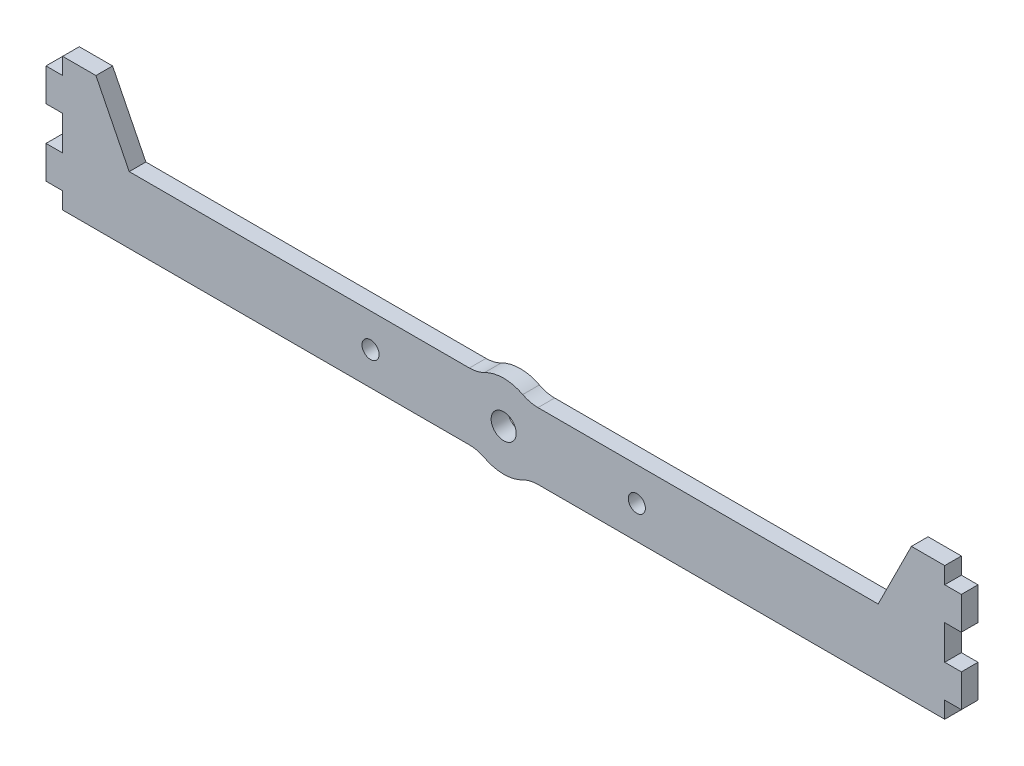
SolidWorks part; units mm, degrees
ref_plane "Front Plane" through (0, 0, 0) normal (0, 0, 1) x (1, 0, 0)
ref_plane "Top Plane" through (0, 0, 0) normal (0, 1, 0) x (1, 0, 0)
ref_plane "Right Plane" through (0, 0, 0) normal (1, 0, 0) x (0, 0, -1)
sketch "Sketch1" plane through (0, 0, 0) normal (0, 0, 1) x (1, 0, 0)
  line L0 (-168.275, -12.7) -> (-168.275, -6.35)
  line L1 (142.875, -12.7) -> (9.525, -12.7)
  line L2 (-142.875, -12.7) -> (-168.275, -12.7)
  line L3 (142.875, 12.7) -> (9.525, 12.7)
  line L4 (-168.275, 12.7) -> (-168.275, 19.25)
  line L5 (168.275, -12.7) -> (-168.275, 12.7) construction
  line L6 (168.275, 12.7) -> (-168.275, -12.7) construction
  line L7 (-168.275, 38.1) -> (-155.575, 38.1)
  line L8 (-155.575, 38.1) -> (-142.875, 12.7)
  line L9 (168.275, 0) -> (-168.275, 0) construction
  line L10 (-168.275, -6.35) -> (-174.625, -6.35)
  line L11 (-168.275, 31.75) -> (-174.625, 31.75)
  line L12 (168.275, -12.7) -> (168.275, -6.35)
  line L13 (0, 12.7) -> (0, -12.7) construction
  line L14 (-168.275, 19.25) -> (-174.625, 19.25)
  line L15 (-174.625, 31.75) -> (-174.625, 19.25)
  line L16 (-174.625, -6.35) -> (-174.625, 6.15)
  line L17 (-168.275, 6.15) -> (-174.625, 6.15)
  line L18 (-168.275, 6.15) -> (-168.275, 12.7)
  line L19 (-168.275, 31.75) -> (-168.275, 38.1)
  line L20 (168.275, -6.35) -> (174.625, -6.35)
  line L21 (174.625, -6.35) -> (174.625, 6.15)
  line L22 (168.275, 6.15) -> (174.625, 6.15)
  line L23 (168.275, 6.15) -> (168.275, 12.7)
  line L24 (168.275, 12.7) -> (168.275, 19.25)
  line L25 (174.625, 31.75) -> (174.625, 19.25)
  line L26 (168.275, 19.25) -> (174.625, 19.25)
  line L27 (168.275, 31.75) -> (174.625, 31.75)
  line L28 (168.275, 31.75) -> (168.275, 38.1)
  line L29 (168.275, 38.1) -> (155.575, 38.1)
  line L30 (155.575, 38.1) -> (142.875, 12.7)
  line L31 (142.875, -12.7) -> (168.275, -12.7)
  line L32 (-9.525, 12.7) -> (-142.875, 12.7)
  line L33 (-9.525, -12.7) -> (-142.875, -12.7)
  arc A0 (9.525, 12.7) -> (-9.525, 12.7) centre (0, 0) ccw
  arc A1 (-9.525, -12.7) -> (9.525, -12.7) centre (0, 0) ccw
  point P0 (0, 0)
  dimension "D1" = 25.4
  dimension "D2" = 336.55
  dimension "D3" = 25.4
  dimension "D4" = 6.35
  dimension "D5" = 12.5
  dimension "D6" = 6.35
  dimension "D7" = 25.4
extrude "Boss-Extrude1" add sketch "Sketch1" along normal blind 6.35
hole_wizard "V (0.377) Diameter Hole1" positions "Sketch3" profile "Sketch2" hole size "V" standard "ANSI Inch" end condition through all
sketch "Sketch3" plane through (0, 0, 6.35) normal (0, 0, 1) x (1, 0, 0)
  point P0 (0, 0)
sketch "Sketch2" plane through (0, 0, 6.35) normal (1, 0, 0) x (0, -1, 0)
  line L0 (0, 0) -> (0, 6.35)
  line L1 (0, 6.35) -> (4.7879, 6.35)
  line L2 (4.7879, 6.35) -> (4.7879, 0)
  line L5 (4.7879, 0) -> (0, 0)
  line L11 (0, -6.35) -> (0, 107.95) construction
  dimension "Thru Hole Dia." = 9.5758
  dimension "Thru Hole Depth" = 6.35
fillet "Fillet1" [suppressed] radius 2.54
fillet "Fillet2" radius 12.7 4 edges at (-9.525, -12.7, 3.175) (9.525, -12.7, 3.175) (9.525, 12.7, 3.175) (-9.525, 12.7, 3.175)
hole_wizard "F (0.257) Diameter Hole1" positions "Sketch5" profile "Sketch4" hole size "F" standard "ANSI Inch" end condition through all
sketch "Sketch5" plane through (0, 0, 6.35) normal (0, 0, 1) x (1, 0, 0)
  line L0 (-174.625, -0.1) -> (174.625, -0.1) construction
  line L1 (-174.625, -6.35) -> (-174.625, 6.15) construction
  line L2 (174.625, -6.35) -> (174.625, 6.15) construction
  line L3 (0, -15.875) -> (0, 15.875) construction
  arc A0 (-7.2727, -14.1111) -> (7.2727, -14.1111) centre (0, 0) ccw construction
  arc A1 (7.2727, 14.1111) -> (-7.2727, 14.1111) centre (0, 0) ccw construction
  point P17 (-50.8, -0.1)
  point P21 (50.8, -0.1)
  dimension "D2" = 50.8
  dimension "D4" = 50.8
sketch "Sketch4" plane through (-50.8, -0.1, 6.35) normal (1, 0, 0) x (0, -1, 0)
  line L0 (0, 0) -> (0, 6.35)
  line L1 (0, 6.35) -> (3.2639, 6.35)
  line L2 (3.2639, 6.35) -> (3.2639, 0)
  line L5 (3.2639, 0) -> (0, 0)
  line L11 (0, -6.35) -> (0, 107.95) construction
  dimension "Thru Hole Dia." = 6.5278
  dimension "Thru Hole Depth" = 6.35
